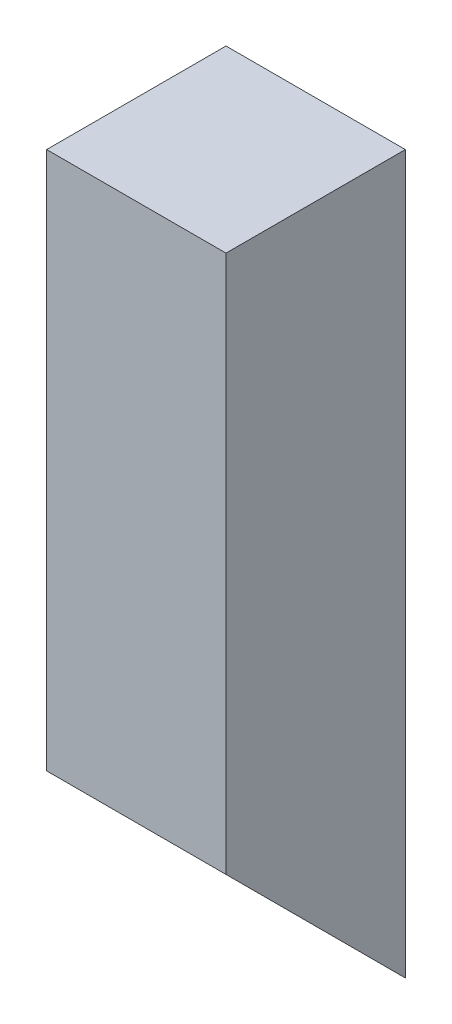
SolidWorks part; units mm, degrees
material "Pine"
ref_plane "Front Plane" through (0, 0, 0) normal (0, 0, 1) x (1, 0, 0)
ref_plane "Top Plane" through (0, 0, 0) normal (0, 1, 0) x (1, 0, 0)
ref_plane "Right Plane" through (0, 0, 0) normal (1, 0, 0) x (0, 0, -1)
sketch "Sketch1" plane through (0, 0, 0) normal (0, 1, 0) x (1, 0, 0)
  line L1 (0, 0) -> (88.9, 0)
  line L2 (0, 0) -> (0, 88.9)
  line L3 (0, 88.9) -> (88.9, 88.9)
  line L4 (88.9, 0) -> (88.9, 88.9)
  dimension "D1" = 88.9
extrude "Boss-Extrude1" add sketch "Sketch1" along normal blind 355.6
sketch "Sketch3" plane through (88.9, 0, 0) normal (1, 0, 0) x (0, 0, -1)
  line L0 (88.9, 0) -> (0, 88.9)
  line L1 (88.9, 0) -> (0, 0)
  line L2 (88.9, 0) -> (88.9, 355.6)
  line L3 (88.9, 355.6) -> (0, 355.6)
  line L4 (0, 0) -> (0, 355.6)
  line M6 (0, 0) -> (88.9, 0)
  line M9 (0, 355.6) -> (0, 0)
  dimension "D1" = 45
extrude "Cut-Extrude1" cut sketch "Sketch3" against normal blind 406.4 contours L0 M6 M9
